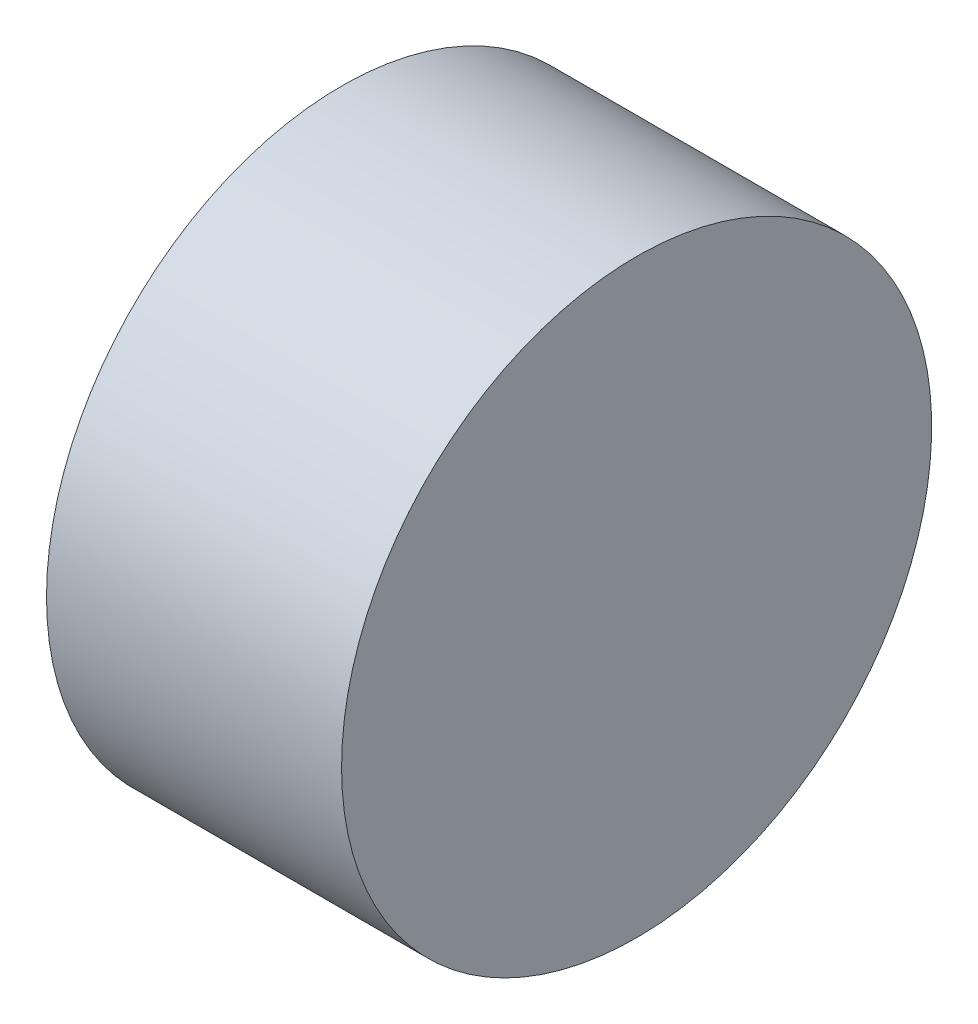
SolidWorks part; units mm, degrees
ref_plane "前视基准面" through (0, 0, 0) normal (0, 0, 1) x (1, 0, 0)
ref_plane "上视基准面" through (0, 0, 0) normal (0, 1, 0) x (1, 0, 0)
ref_plane "右视基准面" through (0, 0, 0) normal (1, 0, 0) x (0, 0, -1)
other "Configuration Table"
sketch "草图1" plane through (0, 0, 0) normal (0, 1, 0) x (1, 0, 0)
  line L0 (-30.4623, -5.2313) -> (0, -27.5421) construction
  line L1 (50, -50) -> (-50, -50)
  line L2 (50, -50) -> (50, 50)
  line L3 (50, 50) -> (-50, 50) construction
  line L4 (-50, -50) -> (-50, 50)
  line L5 (50, -50) -> (-50, 50) construction
  line L6 (50, 50) -> (-50, -50) construction
  line L7 (-50, 50) -> (50, 50)
  point P0 (0, 0)
  dimension "D1" = 100
revolve "旋转1" add sketch "草图1" angle 360 about L7
